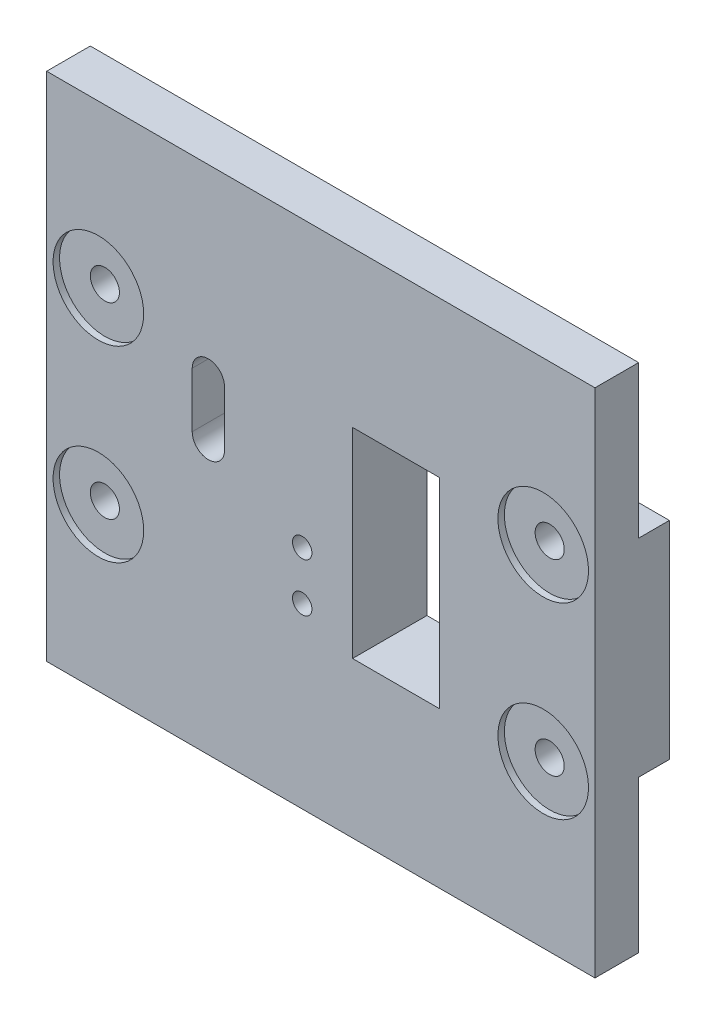
SolidWorks part; units mm, degrees
ref_plane "FP" through (0, 0, 0) normal (0, 0, 1) x (1, 0, 0)
ref_plane "TP" through (0, 0, 0) normal (0, 1, 0) x (1, 0, 0)
ref_plane "RP" through (0, 0, 0) normal (1, 0, 0) x (0, 0, -1)
sketch "Sketch2" plane through (0, 0, 0) normal (0, 0, 1) x (1, 0, 0)
  line L1 (-50, -79) -> (119.5, -79)
  line L2 (-50, -79) -> (-50, 79)
  line L3 (-50, 79) -> (119.5, 79)
  line L4 (119.5, -79) -> (119.5, 79)
  line L12 (-5, 22) -> (-5, 5)
  line L13 (5, 5) -> (5, 22)
  line L14 (-5, 22) -> (-5, 5)
  line L15 (5, 5) -> (5, 22)
  line L28 (44.56, -30.94) -> (71.44, -30.94)
  line L29 (44.56, 30.94) -> (44.56, -30.94)
  line L30 (71.44, 30.94) -> (44.56, 30.94)
  line L31 (71.44, -30.94) -> (71.44, 30.94)
  line L32 (44.56, -30.94) -> (71.44, -30.94)
  line L33 (44.56, 30.94) -> (44.56, -30.94)
  line L34 (71.44, 30.94) -> (44.56, 30.94)
  line L35 (71.44, -30.94) -> (71.44, 30.94)
  arc A9 (-5, 5) -> (5, 5) centre (0, 5) ccw
  arc A10 (5, 22) -> (-5, 22) centre (0, 22) ccw
  arc A11 (-5, 5) -> (5, 5) centre (0, 5) ccw
  arc A12 (5, 22) -> (-5, 22) centre (0, 22) ccw
  circle A13 centre (29, -9) radius 3
  circle A14 centre (29, -9) radius 3
  circle A16 centre (29, -24) radius 3
  circle A17 centre (29, -24) radius 3
  dimension "D1" = 1
  dimension "D2" = 1
  dimension "D3" = 1
  dimension "D4" = 1
extrude "Boss-Extrude1" add sketch "Sketch2" along normal blind 23
sketch "Sketch3" plane through (119.5, 0, 0) normal (1, 0, 0) x (0, 0, -1)
  line L0 (-23, 79) -> (0, 79) construction
  line L1 (-9.5, 32) -> (0, 32)
  line L2 (-9.5, 32) -> (-9.5, 79)
  line L3 (-9.5, 79) -> (0, 79)
  line L4 (0, 32) -> (0, 79)
  line L5 (0, -79) -> (0, 79) construction
  line L6 (-9, 32) -> (-9, 79) construction
  line L7 (0, 0) -> (-35.7154, 0) construction
  line L8 (0, -32) -> (0, -79)
  line L9 (-9.5, -79) -> (0, -79)
  line L10 (-9.5, -32) -> (-9.5, -79)
  line L11 (-9.5, -32) -> (0, -32)
  dimension "D1" = 0.5
  dimension "D2" = 47
extrude "Cut-Extrude1" cut sketch "Sketch3" against normal through all both and the other way through all
sketch "Sketch4" plane through (0, 0, 0) normal (0, 0, 1) x (1, 0, 0)
  circle A0 centre (74.5, -27) radius 2 construction
  circle A1 centre (74.5, 23) radius 2 construction
  circle A2 centre (27, 18.5) radius 2 construction
  circle A3 centre (27, 8.5) radius 2 construction
  circle A4 centre (74.5, -27) radius 2
  circle A5 centre (74.5, 23) radius 2
  circle A6 centre (27, 18.5) radius 2
  circle A7 centre (27, 8.5) radius 2
extrude "Cut-Extrude2" cut sketch "Sketch4" along normal blind 7.5
sketch "Sketch6" plane through (0, 0, 23) normal (0, 0, 1) x (1, 0, 0)
  line L0 (-50, 79) -> (-50, -79) construction
  line L5 (-50, -79) -> (119.5, -79) construction
  line L6 (119.5, 79) -> (-50, 79) construction
  line L7 (119.5, -79) -> (119.5, 79) construction
  circle A0 centre (103.5, 29) radius 14
  circle A1 centre (103.5, -29) radius 14
  circle A2 centre (-34, 29) radius 14
  circle A3 centre (-34, -29) radius 14
  dimension "D1" = 28
  dimension "D2" = 16
  dimension "D3" = 50
  dimension "D4" = 16
  dimension "D5" = 50
  dimension "D6" = 16
extrude "Cut-Extrude4" cut sketch "Sketch6" against normal blind 2
hole_wizard "M10x1.0 Tapped Hole1" positions "Sketch7" profile "Sketch8" tap size "M10x1.0" standard "ANSI Metric"
sketch "Sketch7" plane through (0, 0, 21) normal (0, 0, 1) x (0.9063, -0.4226, 0)
  point P0 (-43.0704, 11.9139)
  point P1 (-18.5585, -40.6519)
  point P2 (81.5469, 70.0239)
  point P3 (81.5469, 70.0239)
  point P4 (106.0588, 17.4581)
cosmetic thread "Hole Thread1" parameters "D1"=9, "D2"=10
cosmetic thread "Hole Thread2" parameters "D1"=9, "D2"=10
cosmetic thread "Hole Thread3" parameters "D1"=9, "D2"=10
cosmetic thread "Hole Thread4" parameters "D1"=9, "D2"=10
sketch "Sketch8" plane through (-34, 29, 21) normal (1, 0, 0) x (0, -1, 0)
  line L0 (0, 0) -> (0, 12.7039)
  line L1 (0, 12.7039) -> (4.5, 10)
  line L2 (4.5, 10) -> (4.5, 0)
  line L5 (4.5, 0) -> (0, 0)
  line L10 (0, 12.7039) -> (-4.5, 10) construction
  line L11 (0, -6.35) -> (0, 107.95) construction
  dimension "Tap Drill Dia." = 9
  dimension "Tap Drill Depth" = 10
  dimension "Drill Angle" = 118
